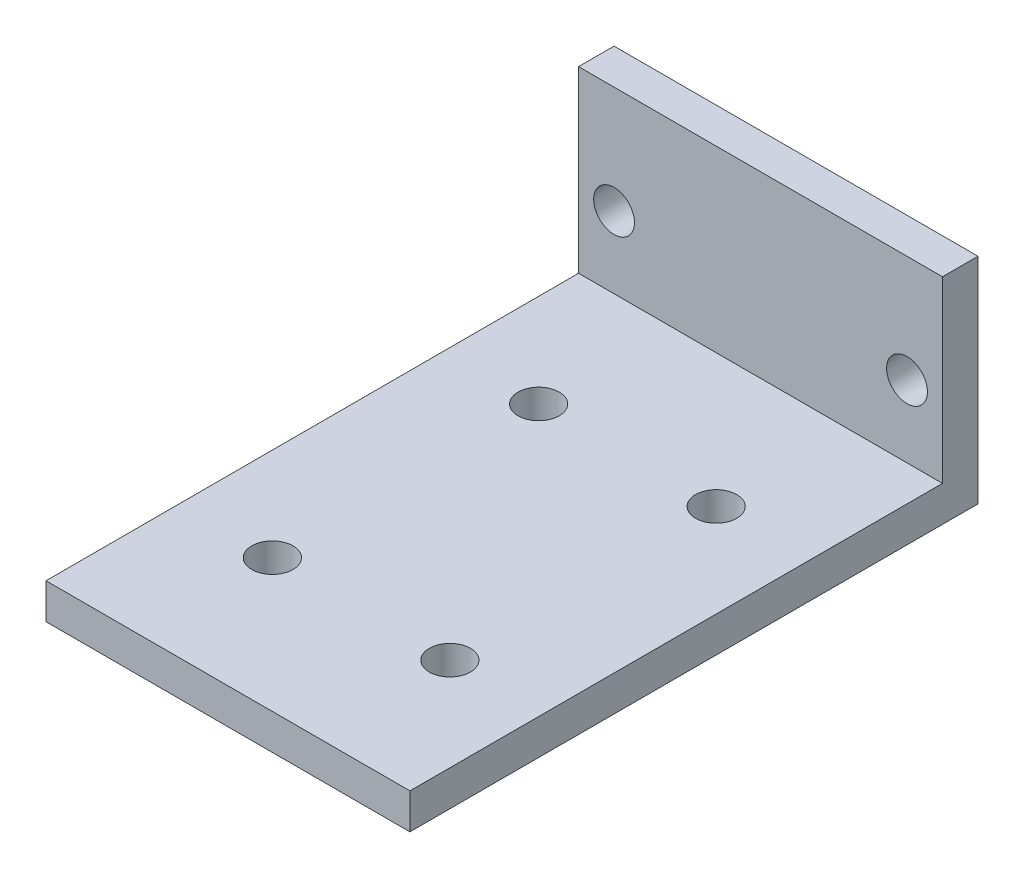
SolidWorks part; units mm, degrees
ref_plane "Front Plane" through (0, 0, 0) normal (0, 0, 1) x (1, 0, 0)
ref_plane "Top Plane" through (0, 0, 0) normal (0, 1, 0) x (1, 0, 0)
ref_plane "Right Plane" through (0, 0, 0) normal (1, 0, 0) x (0, 0, -1)
sketch "Sketch2" plane through (0, 0, 0) normal (0, 0, 1) x (1, 0, 0)
  line L1 (-13.0175, 7.6708) -> (13.0175, 7.6708)
  line L2 (-13.0175, 7.6708) -> (-13.0175, -7.6708)
  line L3 (-13.0175, -7.6708) -> (13.0175, -7.6708)
  line L4 (13.0175, 7.6708) -> (13.0175, -7.6708)
  circle A0 centre (-10.4775, 0) radius 1.4605
  circle A1 centre (10.4775, 0) radius 1.4605
  point P9 (-13.0175, 0)
  dimension "D1" = 2.921
  dimension "D2" = 2.921
  dimension "D3" = 20.955
  dimension "D4" = 10.4775
  dimension "D5" = 7.6708
  dimension "D6" = 2.54
  dimension "D7" = 2.54
extrude "Boss-Extrude1" add sketch "Sketch2" along normal blind 2.54
sketch "Sketch3" plane through (0, 0, 2.54) normal (0, 0, 1) x (1, 0, 0)
  line L0 (13.0175, -7.6708) -> (13.0175, 7.6708) construction
  line L1 (-13.0175, -7.6708) -> (13.0175, -7.6708)
  line L2 (-13.0175, -7.6708) -> (-13.0175, -5.1308)
  line L3 (-13.0175, -5.1308) -> (13.0175, -5.1308)
  line L4 (13.0175, -7.6708) -> (13.0175, -5.1308)
  dimension "D1" = 2.54
extrude "Boss-Extrude2" add sketch "Sketch3" along normal blind 38.1
sketch "Sketch5" plane through (0, -5.1308, 0) normal (0, 1, 0) x (1, 0, 0)
  line L0 (-6.35, -12.065) -> (6.35, -12.065) construction
  line L1 (6.35, -12.065) -> (6.35, -31.115) construction
  line L3 (13.0175, -40.64) -> (13.0175, -2.54) construction
  point P0 (-6.35, -12.065)
  point P1 (6.35, -12.065)
  point P2 (-6.35, -31.115)
  point P3 (6.35, -31.115)
  point P9 (13.0175, -21.59)
  point P10 (6.35, -21.59)
  point P11 (0, 0)
  point P12 (0, -12.065)
  dimension "D1" = 12.7
  dimension "D2" = 19.05
hole_wizard "#4 Clearance Hole1" positions "Sketch6" profile "Sketch7" hole size "#4" standard "ANSI Inch"
sketch "Sketch6" plane through (0, -5.1308, 0) normal (0, 1, 0) x (1, 0, 0)
  point P0 (-6.35, -12.065)
  point P3 (6.35, -12.065)
  point P6 (-6.35, -31.115)
  point P9 (6.35, -31.115)
sketch "Sketch7" plane through (-6.35, -5.1308, 12.065) normal (1, 0, 0) x (0, 0, 1)
  line L0 (0, 0) -> (0, 8.5052)
  line L1 (0, 8.5052) -> (1.4732, 7.62)
  line L2 (1.4732, 7.62) -> (1.4732, 0)
  line L5 (1.4732, 0) -> (0, 0)
  line L10 (0, 8.5052) -> (-1.4732, 7.62) construction
  line L11 (0, -6.35) -> (0, 107.95) construction
  dimension "Hole Dia." = 2.9464
  dimension "Hole Depth" = 7.62
  dimension "Drill Angle" = 118
